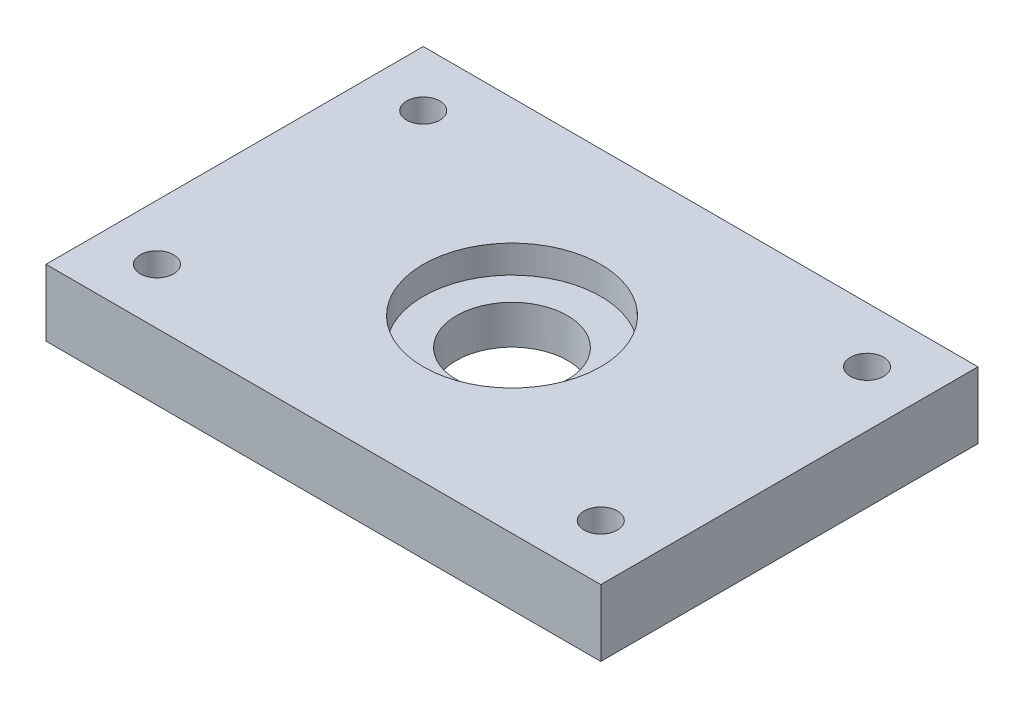
SolidWorks part; units mm, degrees
material "Acrylic (Medium-high impact)"
ref_plane "Front Plane" through (0, 0, 0) normal (0, 0, 1) x (1, 0, 0)
ref_plane "Top Plane" through (0, 0, 0) normal (0, 1, 0) x (1, 0, 0)
ref_plane "Right Plane" through (0, 0, 0) normal (1, 0, 0) x (0, 0, -1)
sketch "Sketch1" plane through (0, 0, 0) normal (0, 1, 0) x (1, 0, 0)
  line L0 (0, 0) -> (0, 17) construction
  line L1 (0, 0) -> (0, -17) construction
  line L2 (0, 0) -> (25, 0) construction
  line L3 (0, 0) -> (-25, 0) construction
  line L5 (25, 17) -> (-25, 17)
  line L6 (25, 17) -> (25, -17)
  line L7 (25, -17) -> (-25, -17)
  line L8 (-25, 17) -> (-25, -17)
  dimension "D1" = 50
  dimension "D2" = 34
extrude "Bearing Holder Plate Boss-Extrude1" add sketch "Sketch1" along normal blind 6
sketch "Sketch3" plane through (0, 0, 0) normal (0, -1, 0) x (1, 0, 0)
  line L0 (0, 0) -> (-20, 12) construction
  line L1 (20, 12) -> (-20, 12) construction
  line L2 (20, 12) -> (20, -12) construction
  line L3 (20, -12) -> (-20, -12) construction
  line L4 (-20, 12) -> (-20, -12) construction
  line L5 (0, 0) -> (-20, -12) construction
  line L6 (0, 0) -> (20, -12) construction
  line L7 (0, 0) -> (20, 12) construction
  line L8 (-25, 17) -> (25, 17) construction
  line L9 (25, 17) -> (25, -17) construction
  circle A0 centre (20, 12) radius 1.5
  circle A1 centre (-20, 12) radius 1.5
  circle A2 centre (-20, -12) radius 1.5
  circle A3 centre (20, -12) radius 1.5
  dimension "D3" = 3
  dimension "D1" = 5
  dimension "D2" = 5
extrude "Mounting Holes Cut-Extrude1" cut sketch "Sketch3" against normal up to surface (6 mm away) up to face at (0, 6, 0)
sketch "Sketch4" plane through (0, 6, 0) normal (0, 1, 0) x (1, 0, 0)
  circle A0 centre (0, 0) radius 5
  dimension "D1" = 10
extrude "Shaft Cut-Extrude2" cut sketch "Sketch4" against normal up to surface (6 mm away) up to face at (20, 0, -13.5)
sketch "Sketch5" plane through (0, 6, 0) normal (0, 1, 0) x (1, 0, 0)
  circle A0 centre (0, 0) radius 8
  dimension "D1" = 16
extrude "Bearing Cut-Extrude3" cut sketch "Sketch5" against normal blind 2.5
